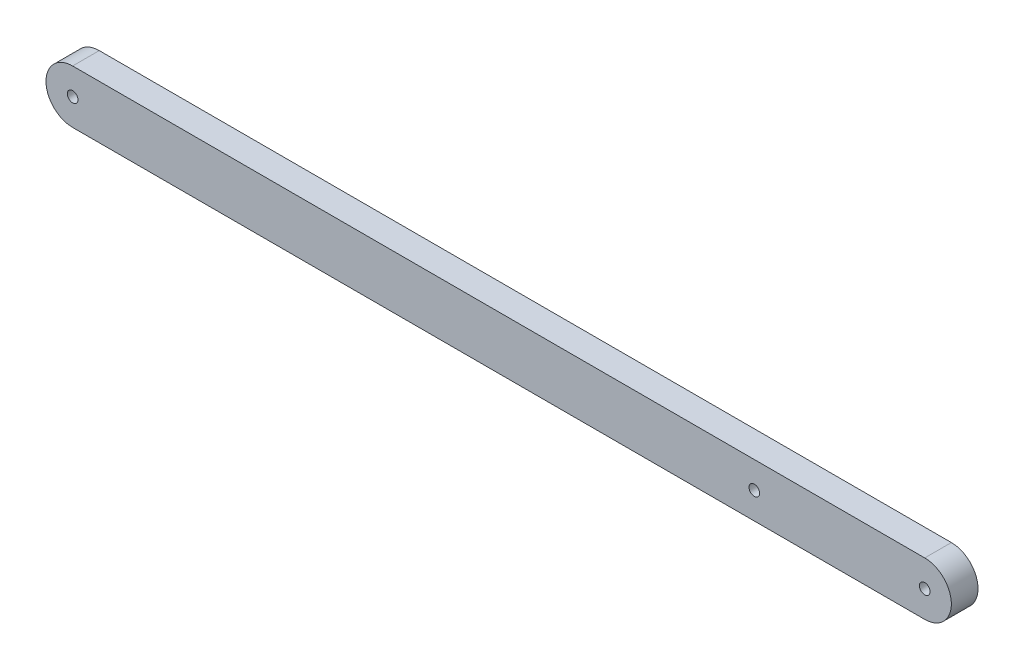
SolidWorks part; units mm, degrees
ref_plane "Front Plane" through (0, 0, 0) normal (0, 0, 1) x (1, 0, 0)
ref_plane "Top Plane" through (0, 0, 0) normal (0, 1, 0) x (1, 0, 0)
ref_plane "Right Plane" through (0, 0, 0) normal (1, 0, 0) x (0, 0, -1)
sketch "Sketch1" plane through (0, 0, 0) normal (0, 0, 1) x (1, 0, 0)
  line L0 (126.7672, 7.5042) -> (-193.2328, 7.5042) construction
  line L1 (126.7672, -2.4958) -> (-193.2328, -2.4958)
  line L2 (126.7672, 17.5042) -> (-193.2328, 17.5042)
  arc A0 (126.7672, -2.4958) -> (126.7672, 17.5042) centre (126.7672, 7.5042) ccw
  arc A1 (-193.2328, 17.5042) -> (-193.2328, -2.4958) centre (-193.2328, 7.5042) ccw
  circle A2 centre (-193.2328, 7.5042) radius 2
  circle A3 centre (126.7672, 7.5042) radius 2
  circle A4 centre (62.7672, 7.5042) radius 2
  point P2 (-33.2328, 7.5042)
  dimension "D2" = 10
  dimension "D3" = 64
  dimension "D1" = 320
extrude "Boss-Extrude1" add sketch "Sketch1" along normal blind 10
